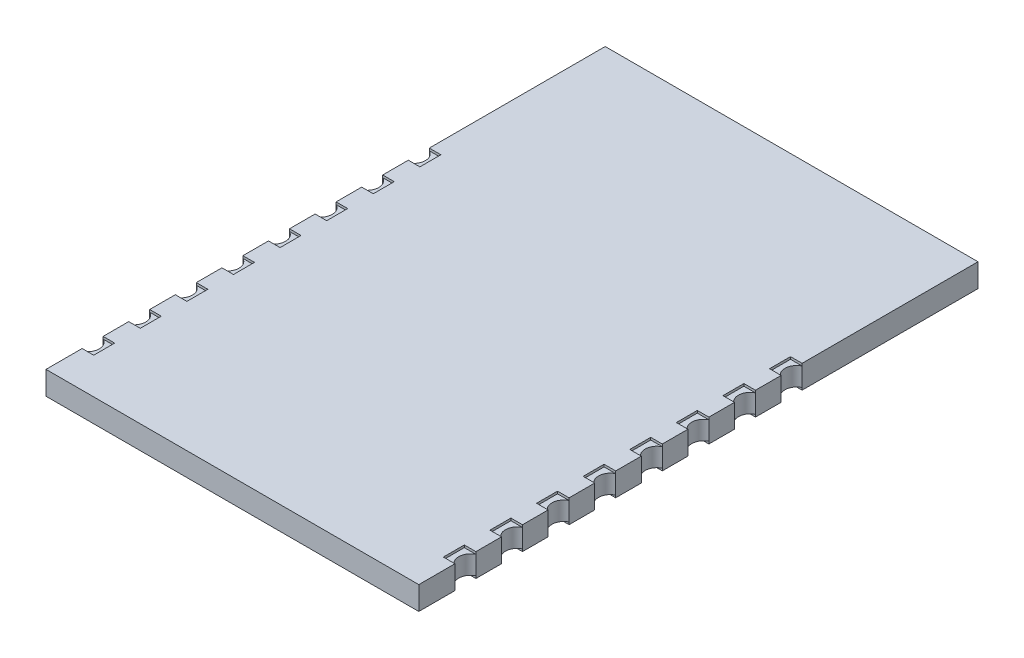
SolidWorks part; units mm, degrees
ref_plane "前基準面" through (0, 0, 0) normal (0, 0, 1) x (1, 0, 0)
ref_plane "上基準面" through (0, 0, 0) normal (0, 1, 0) x (1, 0, 0)
ref_plane "右基準面" through (0, 0, 0) normal (1, 0, 0) x (0, 0, -1)
sketch "草圖1" plane through (0, 0, 0) normal (0, 1, 0) x (1, 0, 0)
  line L5 (-8, 12) -> (8, 12)
  line L6 (-8, 12) -> (-8, -12)
  line L7 (-8, -12) -> (8, -12)
  line L8 (8, 12) -> (8, -12)
  line L9 (-8, 12) -> (8, -12) construction
  line L10 (-8, -12) -> (8, 12) construction
  point P0 (0, 0)
  dimension "D1" = 16
  dimension "24" = 24
extrude "填料-伸長1" add sketch "草圖1" along normal blind 1
sketch "草圖2" plane through (0, 1, 0) normal (0, 1, 0) x (1, 0, 0)
  line L0 (0, 0) -> (0, -5.3119)
  line L1 (-8.003, -9.55) -> (-7.503, -9.55)
  line L2 (-8.003, -9.55) -> (-8.003, -10.45)
  line L3 (-8.003, -10.45) -> (-7.503, -10.45)
  line L4 (-7.503, -9.55) -> (-7.503, -10.45)
  line L5 (8.003, -10.45) -> (7.503, -10.45)
  line L6 (7.503, -9.55) -> (7.503, -10.45)
  line L7 (8.003, -9.55) -> (7.503, -9.55)
  line L8 (8.003, -9.55) -> (8.003, -10.45)
  line L9 (-8.003, -7.55) -> (-8.003, -8.45)
  line L10 (-8.003, -7.55) -> (-7.503, -7.55)
  line L11 (-7.503, -7.55) -> (-7.503, -8.45)
  line L12 (-8.003, -8.45) -> (-7.503, -8.45)
  line L13 (-8.003, -5.55) -> (-8.003, -6.45)
  line L14 (-8.003, -5.55) -> (-7.503, -5.55)
  line L15 (-7.503, -5.55) -> (-7.503, -6.45)
  line L16 (-8.003, -6.45) -> (-7.503, -6.45)
  line L17 (-8.003, -3.55) -> (-8.003, -4.45)
  line L18 (-8.003, -3.55) -> (-7.503, -3.55)
  line L19 (-7.503, -3.55) -> (-7.503, -4.45)
  line L20 (-8.003, -4.45) -> (-7.503, -4.45)
  line L21 (-8.003, -1.55) -> (-8.003, -2.45)
  line L22 (-8.003, -1.55) -> (-7.503, -1.55)
  line L23 (-7.503, -1.55) -> (-7.503, -2.45)
  line L24 (-8.003, -2.45) -> (-7.503, -2.45)
  line L25 (-8.003, 0.45) -> (-8.003, -0.45)
  line L26 (-8.003, 0.45) -> (-7.503, 0.45)
  line L27 (-7.503, 0.45) -> (-7.503, -0.45)
  line L28 (-8.003, -0.45) -> (-7.503, -0.45)
  line L29 (-8.003, 2.45) -> (-8.003, 1.55)
  line L30 (-8.003, 2.45) -> (-7.503, 2.45)
  line L31 (-7.503, 2.45) -> (-7.503, 1.55)
  line L32 (-8.003, 1.55) -> (-7.503, 1.55)
  line L33 (-8.003, 4.45) -> (-8.003, 3.55)
  line L34 (-8.003, 4.45) -> (-7.503, 4.45)
  line L35 (-7.503, 4.45) -> (-7.503, 3.55)
  line L36 (-8.003, 3.55) -> (-7.503, 3.55)
  line L42 (8.003, -8.45) -> (7.503, -8.45)
  line L43 (7.503, -7.55) -> (7.503, -8.45)
  line L44 (8.003, -7.55) -> (7.503, -7.55)
  line L45 (8.003, -7.55) -> (8.003, -8.45)
  line L46 (8.003, -6.45) -> (7.503, -6.45)
  line L47 (7.503, -5.55) -> (7.503, -6.45)
  line L48 (8.003, -5.55) -> (7.503, -5.55)
  line L49 (8.003, -5.55) -> (8.003, -6.45)
  line L50 (8.003, -4.45) -> (7.503, -4.45)
  line L51 (7.503, -3.55) -> (7.503, -4.45)
  line L52 (8.003, -3.55) -> (7.503, -3.55)
  line L53 (8.003, -3.55) -> (8.003, -4.45)
  line L54 (8.003, -2.45) -> (7.503, -2.45)
  line L55 (7.503, -1.55) -> (7.503, -2.45)
  line L56 (8.003, -1.55) -> (7.503, -1.55)
  line L57 (8.003, -1.55) -> (8.003, -2.45)
  line L58 (8.003, -0.45) -> (7.503, -0.45)
  line L59 (7.503, 0.45) -> (7.503, -0.45)
  line L60 (8.003, 0.45) -> (7.503, 0.45)
  line L61 (8.003, 0.45) -> (8.003, -0.45)
  line L62 (8.003, 1.55) -> (7.503, 1.55)
  line L63 (7.503, 2.45) -> (7.503, 1.55)
  line L64 (8.003, 2.45) -> (7.503, 2.45)
  line L65 (8.003, 2.45) -> (8.003, 1.55)
  line L66 (8.003, 3.55) -> (7.503, 3.55)
  line L67 (7.503, 4.45) -> (7.503, 3.55)
  line L68 (8.003, 4.45) -> (7.503, 4.45)
  line L69 (8.003, 4.45) -> (8.003, 3.55)
  point P4 (-8.003, -10)
  line M6 (8, -12) -> (8, 12)
  line M8 (-8, 12) -> (-8, -12)
  dimension "D1" = 2
  dimension "D2" = 8
  dimension "D3" = 8
extrude "除料-伸長1" cut sketch "草圖2" against normal blind 0.1 contours L32 L31 L30 M8 | L28 L27 L26 M8 | L24 L23 L22 M8 | L20 L19 L18 M8 | L16 L15 L14 M8 | L12 L11 L10 M8 | L4 L1 L3 M8 | L7 L6 L5 M6 | L44 L43 L42 M6 | L48 L47 L46 M6 | L52 L51 L50 M6 | L56 L55 L54 M6 | L60 L59 L58 M6 | L68 L67 L66 M6 | L64 L63 L62 M6 | L35 L36 L33 L34
sketch "草圖3" plane through (0, 0, 0) normal (0, -1, 0) x (1, 0, 0)
  line L0 (7, 7.55) -> (7, 8.45)
  line L1 (8, 12) -> (8, -12) construction
  line L6 (7, 9.55) -> (8, 9.55)
  line L7 (7, 9.55) -> (7, 10.45)
  line L8 (7, 10.45) -> (8, 10.45)
  line L9 (8, 9.55) -> (8, 10.45)
  line L10 (-8, 12) -> (8, 12) construction
  line L11 (7, 7.55) -> (8, 7.55)
  line L12 (8, 7.55) -> (8, 8.45)
  line L13 (7, 8.45) -> (8, 8.45)
  line L14 (7, 5.55) -> (7, 6.45)
  line L15 (7, 5.55) -> (8, 5.55)
  line L16 (8, 5.55) -> (8, 6.45)
  line L17 (7, 6.45) -> (8, 6.45)
  line L18 (7, 3.55) -> (7, 4.45)
  line L19 (7, 3.55) -> (8, 3.55)
  line L20 (8, 3.55) -> (8, 4.45)
  line L21 (7, 4.45) -> (8, 4.45)
  line L22 (7, 1.55) -> (7, 2.45)
  line L23 (7, 1.55) -> (8, 1.55)
  line L24 (8, 1.55) -> (8, 2.45)
  line L25 (7, 2.45) -> (8, 2.45)
  line L26 (7, -0.45) -> (7, 0.45)
  line L27 (7, -0.45) -> (8, -0.45)
  line L28 (8, -0.45) -> (8, 0.45)
  line L29 (7, 0.45) -> (8, 0.45)
  line L30 (7, -2.45) -> (7, -1.55)
  line L31 (7, -2.45) -> (8, -2.45)
  line L32 (8, -2.45) -> (8, -1.55)
  line L33 (7, -1.55) -> (8, -1.55)
  line L34 (7, -4.45) -> (7, -3.55)
  line L35 (7, -4.45) -> (8, -4.45)
  line L36 (8, -4.45) -> (8, -3.55)
  line L37 (7, -3.55) -> (8, -3.55)
  line L38 (0, 0) -> (0, -2.1829)
  line L39 (-7, 10.45) -> (-8, 10.45)
  line L40 (-8, 9.55) -> (-8, 10.45)
  line L41 (-7, 9.55) -> (-8, 9.55)
  line L42 (-7, 9.55) -> (-7, 10.45)
  line L43 (-7, -4.45) -> (-8, -4.45)
  line L44 (-8, -4.45) -> (-8, -3.55)
  line L45 (-7, -3.55) -> (-8, -3.55)
  line L46 (-7, -4.45) -> (-7, -3.55)
  line L47 (-7, -2.45) -> (-8, -2.45)
  line L48 (-8, -2.45) -> (-8, -1.55)
  line L49 (-7, -1.55) -> (-8, -1.55)
  line L50 (-7, -2.45) -> (-7, -1.55)
  line L51 (-7, -0.45) -> (-8, -0.45)
  line L52 (-8, -0.45) -> (-8, 0.45)
  line L53 (-7, 0.45) -> (-8, 0.45)
  line L54 (-7, -0.45) -> (-7, 0.45)
  line L55 (-7, 1.55) -> (-8, 1.55)
  line L56 (-8, 1.55) -> (-8, 2.45)
  line L57 (-7, 2.45) -> (-8, 2.45)
  line L58 (-7, 1.55) -> (-7, 2.45)
  line L59 (-7, 3.55) -> (-8, 3.55)
  line L60 (-8, 3.55) -> (-8, 4.45)
  line L61 (-7, 4.45) -> (-8, 4.45)
  line L62 (-7, 3.55) -> (-7, 4.45)
  line L63 (-7, 5.55) -> (-8, 5.55)
  line L64 (-8, 5.55) -> (-8, 6.45)
  line L65 (-7, 6.45) -> (-8, 6.45)
  line L66 (-7, 5.55) -> (-7, 6.45)
  line L67 (-7, 7.55) -> (-8, 7.55)
  line L68 (-8, 7.55) -> (-8, 8.45)
  line L69 (-7, 8.45) -> (-8, 8.45)
  line L70 (-7, 7.55) -> (-7, 8.45)
  point P8 (8, 10)
  dimension "D1" = 2
  dimension "D2" = 0.9
  dimension "D3" = 8
extrude "除料-伸長2" cut sketch "草圖3" against normal blind 0.1 contours L67 L70 L69 L9 | L63 L66 L65 L9 | L59 L62 L61 L9 | L51 L54 L53 L9 | L47 L50 L49 L9 | L43 L46 L45 L9 | L33 L30 L31 L7 | L29 L26 L27 L7 | L25 L22 L23 L7 | L21 L18 L19 L7 | L13 L0 L11 L7 | L8 L7 L6 | L41 L40 L39 L42 | L58 L57 L56 L55 | L36 L37 L34 L35 | L17 L16 L15 L14
sketch "草圖8" plane through (0, 1, 0) normal (0, 1, 0) x (1, 0, 0)
  line L0 (-8, -12) -> (8, -12) construction
  line L1 (-1, 0.6) -> (3.7, 0.6)
  line L2 (-1, 0.6) -> (-1, -4.1)
  line L3 (-1, -4.1) -> (3.7, -4.1)
  line L4 (3.7, 0.6) -> (3.7, -4.1)
  line L5 (-1, 0.6) -> (3.7, -4.1) construction
  line L6 (-1, -4.1) -> (3.7, 0.6) construction
  line L7 (-8, -2.45) -> (-8, -3.55) construction
  point P0 (1.35, -1.75)
  dimension "D1" = 7.9
  dimension "D2" = 7
  dimension "D3" = 4.7
  dimension "D4" = 4.7
extrude "除料-伸長3" cut sketch "草圖8" against normal blind 0.1
sketch "草圖12" plane through (0, 0.9, 0) normal (0, 1, 0) x (1, 0, 0)
  line L0 (-1, 0.6) -> (-1, -4.1) construction
  line L1 (-1, -4.1) -> (3.7, -4.1) construction
  circle A1 centre (-0.51, -3.65) radius 0.2
  circle A2 centre (0.42, -3.65) radius 0.2
  circle A3 centre (1.35, -3.65) radius 0.2
  circle A4 centre (2.28, -3.65) radius 0.2
  circle A5 centre (3.21, -3.65) radius 0.2
  circle A6 centre (-0.51, -2.72) radius 0.2
  circle A7 centre (0.42, -2.72) radius 0.2
  circle A8 centre (1.35, -2.72) radius 0.2
  circle A9 centre (2.28, -2.72) radius 0.2
  circle A10 centre (3.21, -2.72) radius 0.2
  circle A11 centre (-0.51, -1.79) radius 0.2
  circle A12 centre (0.42, -1.79) radius 0.2
  circle A13 centre (1.35, -1.79) radius 0.2
  circle A14 centre (2.28, -1.79) radius 0.2
  circle A15 centre (3.21, -1.79) radius 0.2
  circle A16 centre (-0.51, -0.86) radius 0.2
  circle A17 centre (0.42, -0.86) radius 0.2
  circle A18 centre (1.35, -0.86) radius 0.2
  circle A19 centre (2.28, -0.86) radius 0.2
  circle A20 centre (3.21, -0.86) radius 0.2
  circle A21 centre (-0.51, 0.07) radius 0.2
  circle A22 centre (0.42, 0.07) radius 0.2
  circle A23 centre (1.35, 0.07) radius 0.2
  circle A24 centre (2.28, 0.07) radius 0.2
  circle A25 centre (3.21, 0.07) radius 0.2
  dimension "D1" = 0.49
  dimension "D2" = 0.45
  dimension "D3" = 5
  dimension "D4" = 5
extrude "除料-伸長4" cut sketch "草圖12" against normal blind 0.1
sketch "草圖13" plane through (0, 1, 0) normal (0, 1, 0) x (1, 0, 0)
  line L5 (-1, 0.6) -> (3.7, 0.6)
  line L6 (-1, 0.6) -> (-1, -4.1)
  line L7 (-1, -4.1) -> (3.7, -4.1)
  line L8 (3.7, 0.6) -> (3.7, -4.1)
extrude "填料-伸長2" add sketch "草圖13" against normal blind 0.5
sketch "草圖15" plane through (0, 0, 0) normal (0, -1, 0) x (1, 0, 0)
  line L0 (-8, 12) -> (8, 12) construction
  line L1 (1, -0.6) -> (-3.7, -0.6)
  line L2 (1, -0.6) -> (1, 4.1)
  line L3 (1, 4.1) -> (-3.7, 4.1)
  line L4 (-3.7, -0.6) -> (-3.7, 4.1)
  line L5 (1, -0.6) -> (-3.7, 4.1) construction
  line L6 (1, 4.1) -> (-3.7, -0.6) construction
  line L7 (8, 1.55) -> (8, 0.45) construction
  point P0 (-1.35, 1.75)
  point P9 (8, 1)
  dimension "D1" = 7.9
  dimension "D2" = 7
  dimension "D3" = 4.7
  dimension "D4" = 4.7
extrude "除料-伸長5" cut sketch "草圖15" against normal blind 0.1
sketch "草圖16" plane through (0, 0, 0) normal (0, -1, 0) x (1, 0, 0)
  line L0 (1, 4.1) -> (-3.7, 4.1) construction
  line L1 (1, -0.6) -> (1, 4.1) construction
  circle A0 centre (0.51, 3.61) radius 0.2
  circle A1 centre (-0.42, 3.61) radius 0.2
  circle A2 centre (-1.35, 3.61) radius 0.2
  circle A3 centre (-2.28, 3.61) radius 0.2
  circle A4 centre (-3.21, 3.61) radius 0.2
  circle A5 centre (-3.21, 2.68) radius 0.2
  circle A6 centre (-2.28, 2.68) radius 0.2
  circle A7 centre (-1.35, 2.68) radius 0.2
  circle A8 centre (-0.42, 2.68) radius 0.2
  circle A9 centre (0.51, 2.68) radius 0.2
  circle A10 centre (-3.21, 1.75) radius 0.2
  circle A11 centre (-2.28, 1.75) radius 0.2
  circle A12 centre (-1.35, 1.75) radius 0.2
  circle A13 centre (-0.42, 1.75) radius 0.2
  circle A14 centre (0.51, 1.75) radius 0.2
  circle A15 centre (-3.21, 0.82) radius 0.2
  circle A16 centre (-2.28, 0.82) radius 0.2
  circle A17 centre (-1.35, 0.82) radius 0.2
  circle A18 centre (-0.42, 0.82) radius 0.2
  circle A19 centre (0.51, 0.82) radius 0.2
  circle A20 centre (-3.21, -0.11) radius 0.2
  circle A21 centre (-2.28, -0.11) radius 0.2
  circle A22 centre (-1.35, -0.11) radius 0.2
  circle A23 centre (-0.42, -0.11) radius 0.2
  circle A24 centre (0.51, -0.11) radius 0.2
  dimension "D1" = 0.49
  dimension "D2" = 0.49
  dimension "D3" = 5
  dimension "D4" = 5
extrude "除料-伸長6" cut sketch "草圖16" against normal blind 0.25
sketch "草圖17" plane through (0, 1, 0) normal (0, 1, 0) x (1, 0, 0)
  line L0 (-8, 4.45) -> (-8, 3.55)
  line L1 (-8, 2.45) -> (-8, 1.55)
  line L2 (-8, 0.45) -> (-8, -0.45)
  line L3 (-8, -1.55) -> (-8, -2.45)
  line L4 (-8, -3.55) -> (-8, -4.45)
  line L5 (-8, -5.55) -> (-8, -6.45)
  line L6 (-8, -7.55) -> (-8, -8.45)
  line L7 (-8, -9.55) -> (-8, -10.45)
  line L9 (8, -9.55) -> (8, -10.45)
  line L10 (8, -7.55) -> (8, -8.45)
  line L11 (8, -5.55) -> (8, -6.45)
  line L12 (8, -3.55) -> (8, -4.45)
  line L13 (8, -1.55) -> (8, -2.45)
  line L14 (8, 0.45) -> (8, -0.45)
  line L15 (8, 2.45) -> (8, 1.55)
  line L16 (8, 4.45) -> (8, 3.55)
  arc A0 (-8, 4.45) -> (-8, 3.55) centre (-8.2179, 4) cw
  arc A1 (-8, 2.45) -> (-8, 1.55) centre (-8.2179, 2) cw
  arc A2 (-8, 0.45) -> (-8, -0.45) centre (-8.2179, 0) cw
  arc A3 (-8, -1.55) -> (-8, -2.45) centre (-8.2179, -2) cw
  arc A4 (-8, -3.55) -> (-8, -4.45) centre (-8.2179, -4) cw
  arc A5 (-8, -5.55) -> (-8, -6.45) centre (-8.2179, -6) cw
  arc A6 (-8, -7.55) -> (-8, -8.45) centre (-8.2179, -8) cw
  arc A7 (-8, -9.55) -> (-8, -10.45) centre (-8.2179, -10) cw
  arc A8 (8, -9.55) -> (8, -10.45) centre (8.2179, -10) ccw
  arc A9 (8, -7.55) -> (8, -8.45) centre (8.2179, -8) ccw
  arc A10 (8, -5.55) -> (8, -6.45) centre (8.2179, -6) ccw
  arc A11 (8, -3.55) -> (8, -4.45) centre (8.2179, -4) ccw
  arc A12 (8, -1.55) -> (8, -2.45) centre (8.2179, -2) ccw
  arc A13 (8, 0.45) -> (8, -0.45) centre (8.2179, 0) ccw
  arc A14 (8, 2.45) -> (8, 1.55) centre (8.2179, 2) ccw
  arc A15 (8, 4.45) -> (8, 3.55) centre (8.2179, 4) ccw
  dimension "D1" = 8
extrude "除料-伸長7" cut sketch "草圖17" against normal blind 10
